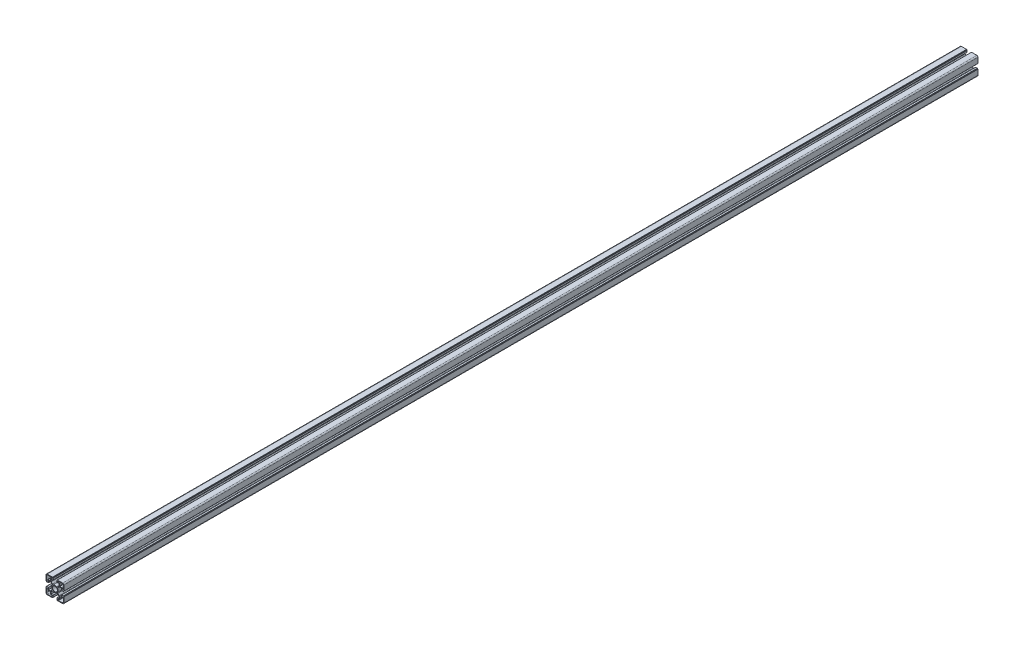
SolidWorks part; units mm, degrees
ref_plane "Front Plane" through (0, 0, 0) normal (0, 0, 1) x (1, 0, 0)
ref_plane "Top Plane" through (0, 0, 0) normal (0, 1, 0) x (1, 0, 0)
ref_plane "Right Plane" through (0, 0, 0) normal (1, 0, 0) x (0, 0, -1)
sketch "Sketch1" plane through (0, 0, 0) normal (0, 0, 1) x (1, 0, 0)
  line L3 (-22.5, 19.5) -> (-22.5, 6.3)
  line L4 (-20.7, 5) -> (-16.7, 5)
  line L5 (-16.5, 5.2) -> (-16.5, 9.8)
  line L6 (-16.3, 10) -> (-11.8642, 10)
  line L7 (-10.4924, 9.4318) -> (-7.2967, 6.236)
  line L8 (-21, 18.5) -> (-21, 9)
  line L9 (-16.5, 5) -> (-16.5, 10) construction
  line L10 (-18, 9) -> (-18, 10.5)
  line L11 (-17, 11.5) -> (-12.5, 11.5)
  line L12 (-22, 5.8) -> (-21.3, 5.8)
  line L13 (-21, 5.5) -> (-21, 5.3)
  line L14 (-21, 22.5) -> (-21, 6.5) construction
  line L15 (-18, 11.5) -> (-10.4393, 11.5) construction
  line L16 (-10.4393, 11.5) -> (-5.1016, 6.1623) construction
  line L17 (-18, 6.5) -> (-18, 11.5) construction
  line L18 (-22.5, 22.5) -> (-22.5, 5) construction
  line L19 (-22.5, 5) -> (-16.5, 5) construction
  line L20 (-21, 6.5) -> (-18, 6.5) construction
  line L21 (-16.5, 10) -> (-11.0607, 10) construction
  line L22 (-11.0607, 10) -> (-6.1623, 5.1016) construction
  line L23 (-5.5, 21) -> (-5.3, 21)
  line L24 (-5.8, 22) -> (-5.8, 21.3)
  line L25 (-11.5, 17) -> (-11.5, 12.5)
  line L26 (-9, 18) -> (-10.5, 18)
  line L27 (-18.5, 21) -> (-9, 21)
  line L28 (-9.4318, 10.4924) -> (-6.236, 7.2967)
  line L29 (-10, 16.3) -> (-10, 11.8642)
  line L30 (-5.2, 16.5) -> (-9.8, 16.5)
  line L31 (-5, 20.7) -> (-5, 16.7)
  line L32 (-19.5, 22.5) -> (-6.3, 22.5)
  line L33 (19.5, 22.5) -> (6.3, 22.5)
  line L34 (5, 20.7) -> (5, 16.7)
  line L35 (5.2, 16.5) -> (9.8, 16.5)
  line L36 (10, 16.3) -> (10, 11.8642)
  line L37 (9.4318, 10.4924) -> (6.236, 7.2967)
  line L38 (18.5, 21) -> (9, 21)
  line L39 (9, 18) -> (10.5, 18)
  line L40 (11.5, 17) -> (11.5, 12.5)
  line L41 (5.8, 22) -> (5.8, 21.3)
  line L42 (5.5, 21) -> (5.3, 21)
  line L43 (21, 5.5) -> (21, 5.3)
  line L44 (22, 5.8) -> (21.3, 5.8)
  line L45 (17, 11.5) -> (12.5, 11.5)
  line L46 (18, 9) -> (18, 10.5)
  line L47 (21, 18.5) -> (21, 9)
  line L48 (10.4924, 9.4318) -> (7.2967, 6.236)
  line L49 (16.3, 10) -> (11.8642, 10)
  line L50 (16.5, 5.2) -> (16.5, 9.8)
  line L51 (20.7, 5) -> (16.7, 5)
  line L52 (22.5, 19.5) -> (22.5, 6.3)
  line L53 (22.5, -19.5) -> (22.5, -6.3)
  line L54 (20.7, -5) -> (16.7, -5)
  line L55 (16.5, -5.2) -> (16.5, -9.8)
  line L56 (16.3, -10) -> (11.8642, -10)
  line L57 (10.4924, -9.4318) -> (7.2967, -6.236)
  line L58 (21, -18.5) -> (21, -9)
  line L59 (18, -9) -> (18, -10.5)
  line L60 (17, -11.5) -> (12.5, -11.5)
  line L61 (22, -5.8) -> (21.3, -5.8)
  line L62 (21, -5.5) -> (21, -5.3)
  line L63 (5.5, -21) -> (5.3, -21)
  line L64 (5.8, -22) -> (5.8, -21.3)
  line L65 (11.5, -17) -> (11.5, -12.5)
  line L66 (9, -18) -> (10.5, -18)
  line L67 (18.5, -21) -> (9, -21)
  line L68 (9.4318, -10.4924) -> (6.236, -7.2967)
  line L69 (10, -16.3) -> (10, -11.8642)
  line L70 (5.2, -16.5) -> (9.8, -16.5)
  line L71 (5, -20.7) -> (5, -16.7)
  line L72 (19.5, -22.5) -> (6.3, -22.5)
  line L73 (-19.5, -22.5) -> (-6.3, -22.5)
  line L74 (-5, -20.7) -> (-5, -16.7)
  line L75 (-5.2, -16.5) -> (-9.8, -16.5)
  line L76 (-10, -16.3) -> (-10, -11.8642)
  line L77 (-9.4318, -10.4924) -> (-6.236, -7.2967)
  line L78 (-18.5, -21) -> (-9, -21)
  line L79 (-9, -18) -> (-10.5, -18)
  line L80 (-11.5, -17) -> (-11.5, -12.5)
  line L81 (-5.8, -22) -> (-5.8, -21.3)
  line L82 (-5.5, -21) -> (-5.3, -21)
  line L83 (-21, -5.5) -> (-21, -5.3)
  line L84 (-22, -5.8) -> (-21.3, -5.8)
  line L85 (-17, -11.5) -> (-12.5, -11.5)
  line L86 (-18, -9) -> (-18, -10.5)
  line L87 (-21, -18.5) -> (-21, -9)
  line L88 (-10.4924, -9.4318) -> (-7.2967, -6.236)
  line L89 (-16.3, -10) -> (-11.8642, -10)
  line L90 (-16.5, -5.2) -> (-16.5, -9.8)
  line L91 (-20.7, -5) -> (-16.7, -5)
  line L92 (-22.5, -19.5) -> (-22.5, -6.3)
  arc A0 (0, 6.1) -> (-6.1, 0) centre (0, 0) ccw
  arc A1 (-6.9766, 3.9149) -> (-8, 0) centre (0, 0) ccw
  arc A2 (-21, 9) -> (-18, 9) centre (-19.5, 9) ccw
  arc A3 (-22, 5.8) -> (-22.5, 6.3) centre (-22, 6.3) cw
  arc A4 (-21, 5.3) -> (-20.7, 5) centre (-20.7, 5.3) ccw
  arc A5 (-21.3, 5.8) -> (-21, 5.5) centre (-21.3, 5.5) cw
  arc A6 (-16.7, 5) -> (-16.5, 5.2) centre (-16.7, 5.2) ccw
  arc A7 (-16.5, 9.8) -> (-16.3, 10) centre (-16.3, 9.8) cw
  arc A8 (-7.2967, 6.236) -> (-6.9766, 3.9149) centre (-8.6685, 4.8643) cw
  arc A9 (-11.8642, 10) -> (-10.4924, 9.4318) centre (-11.8642, 8.06) cw
  arc A10 (-18, 10.5) -> (-17, 11.5) centre (-17, 10.5) cw
  arc A11 (-10.5, 18) -> (-11.5, 17) centre (-10.5, 17) ccw
  arc A12 (-10, 11.8642) -> (-9.4318, 10.4924) centre (-8.06, 11.8642) ccw
  arc A13 (-6.236, 7.2967) -> (-3.9149, 6.9766) centre (-4.8643, 8.6685) ccw
  arc A14 (-9.8, 16.5) -> (-10, 16.3) centre (-9.8, 16.3) ccw
  arc A15 (-5, 16.7) -> (-5.2, 16.5) centre (-5.2, 16.7) cw
  arc A16 (-5.8, 21.3) -> (-5.5, 21) centre (-5.5, 21.3) ccw
  arc A17 (-5.3, 21) -> (-5, 20.7) centre (-5.3, 20.7) cw
  arc A18 (-5.8, 22) -> (-6.3, 22.5) centre (-6.3, 22) ccw
  arc A19 (-9, 21) -> (-9, 18) centre (-9, 19.5) cw
  arc A20 (-3.9149, 6.9766) -> (0, 8) centre (0, 0) cw
  arc A21 (-21, 18.5) -> (-18.5, 21) centre (-18.5, 18.5) cw
  arc A22 (-22.5, 19.5) -> (-19.5, 22.5) centre (-19.5, 19.5) cw
  arc A23 (-12.5, 11.5) -> (-11.5, 12.5) centre (-12.5, 12.5) ccw
  arc A24 (6.1, 0) -> (0, 6.1) centre (0, 0) ccw
  arc A25 (3.9149, 6.9766) -> (0, 8) centre (0, 0) ccw
  arc A26 (9, 21) -> (9, 18) centre (9, 19.5) ccw
  arc A27 (5.8, 22) -> (6.3, 22.5) centre (6.3, 22) cw
  arc A28 (5.3, 21) -> (5, 20.7) centre (5.3, 20.7) ccw
  arc A29 (5.8, 21.3) -> (5.5, 21) centre (5.5, 21.3) cw
  arc A30 (5, 16.7) -> (5.2, 16.5) centre (5.2, 16.7) ccw
  arc A31 (9.8, 16.5) -> (10, 16.3) centre (9.8, 16.3) cw
  arc A32 (6.236, 7.2967) -> (3.9149, 6.9766) centre (4.8643, 8.6685) cw
  arc A33 (10, 11.8642) -> (9.4318, 10.4924) centre (8.06, 11.8642) cw
  arc A34 (10.5, 18) -> (11.5, 17) centre (10.5, 17) cw
  arc A35 (18, 10.5) -> (17, 11.5) centre (17, 10.5) ccw
  arc A36 (11.8642, 10) -> (10.4924, 9.4318) centre (11.8642, 8.06) ccw
  arc A37 (7.2967, 6.236) -> (6.9766, 3.9149) centre (8.6685, 4.8643) ccw
  arc A38 (16.5, 9.8) -> (16.3, 10) centre (16.3, 9.8) ccw
  arc A39 (16.7, 5) -> (16.5, 5.2) centre (16.7, 5.2) cw
  arc A40 (21.3, 5.8) -> (21, 5.5) centre (21.3, 5.5) ccw
  arc A41 (21, 5.3) -> (20.7, 5) centre (20.7, 5.3) cw
  arc A42 (22, 5.8) -> (22.5, 6.3) centre (22, 6.3) ccw
  arc A43 (21, 9) -> (18, 9) centre (19.5, 9) cw
  arc A44 (6.9766, 3.9149) -> (8, 0) centre (0, 0) cw
  arc A45 (18.5, 21) -> (21, 18.5) centre (18.5, 18.5) cw
  arc A46 (19.5, 22.5) -> (22.5, 19.5) centre (19.5, 19.5) cw
  arc A47 (11.5, 12.5) -> (12.5, 11.5) centre (12.5, 12.5) ccw
  arc A48 (0, -6.1) -> (6.1, 0) centre (0, 0) ccw
  arc A49 (6.9766, -3.9149) -> (8, 0) centre (0, 0) ccw
  arc A50 (21, -9) -> (18, -9) centre (19.5, -9) ccw
  arc A51 (22, -5.8) -> (22.5, -6.3) centre (22, -6.3) cw
  arc A52 (21, -5.3) -> (20.7, -5) centre (20.7, -5.3) ccw
  arc A53 (21.3, -5.8) -> (21, -5.5) centre (21.3, -5.5) cw
  arc A54 (16.7, -5) -> (16.5, -5.2) centre (16.7, -5.2) ccw
  arc A55 (16.5, -9.8) -> (16.3, -10) centre (16.3, -9.8) cw
  arc A56 (7.2967, -6.236) -> (6.9766, -3.9149) centre (8.6685, -4.8643) cw
  arc A57 (11.8642, -10) -> (10.4924, -9.4318) centre (11.8642, -8.06) cw
  arc A58 (18, -10.5) -> (17, -11.5) centre (17, -10.5) cw
  arc A59 (10.5, -18) -> (11.5, -17) centre (10.5, -17) ccw
  arc A60 (10, -11.8642) -> (9.4318, -10.4924) centre (8.06, -11.8642) ccw
  arc A61 (6.236, -7.2967) -> (3.9149, -6.9766) centre (4.8643, -8.6685) ccw
  arc A62 (9.8, -16.5) -> (10, -16.3) centre (9.8, -16.3) ccw
  arc A63 (5, -16.7) -> (5.2, -16.5) centre (5.2, -16.7) cw
  arc A64 (5.8, -21.3) -> (5.5, -21) centre (5.5, -21.3) ccw
  arc A65 (5.3, -21) -> (5, -20.7) centre (5.3, -20.7) cw
  arc A66 (5.8, -22) -> (6.3, -22.5) centre (6.3, -22) ccw
  arc A67 (9, -21) -> (9, -18) centre (9, -19.5) cw
  arc A68 (3.9149, -6.9766) -> (0, -8) centre (0, 0) cw
  arc A69 (21, -18.5) -> (18.5, -21) centre (18.5, -18.5) cw
  arc A70 (22.5, -19.5) -> (19.5, -22.5) centre (19.5, -19.5) cw
  arc A71 (12.5, -11.5) -> (11.5, -12.5) centre (12.5, -12.5) ccw
  arc A72 (-6.1, 0) -> (0, -6.1) centre (0, 0) ccw
  arc A73 (-3.9149, -6.9766) -> (0, -8) centre (0, 0) ccw
  arc A74 (-9, -21) -> (-9, -18) centre (-9, -19.5) ccw
  arc A75 (-5.8, -22) -> (-6.3, -22.5) centre (-6.3, -22) cw
  arc A76 (-5.3, -21) -> (-5, -20.7) centre (-5.3, -20.7) ccw
  arc A77 (-5.8, -21.3) -> (-5.5, -21) centre (-5.5, -21.3) cw
  arc A78 (-5, -16.7) -> (-5.2, -16.5) centre (-5.2, -16.7) ccw
  arc A79 (-9.8, -16.5) -> (-10, -16.3) centre (-9.8, -16.3) cw
  arc A80 (-6.236, -7.2967) -> (-3.9149, -6.9766) centre (-4.8643, -8.6685) cw
  arc A81 (-10, -11.8642) -> (-9.4318, -10.4924) centre (-8.06, -11.8642) cw
  arc A82 (-10.5, -18) -> (-11.5, -17) centre (-10.5, -17) cw
  arc A83 (-18, -10.5) -> (-17, -11.5) centre (-17, -10.5) ccw
  arc A84 (-11.8642, -10) -> (-10.4924, -9.4318) centre (-11.8642, -8.06) ccw
  arc A85 (-7.2967, -6.236) -> (-6.9766, -3.9149) centre (-8.6685, -4.8643) ccw
  arc A86 (-16.5, -9.8) -> (-16.3, -10) centre (-16.3, -9.8) ccw
  arc A87 (-16.7, -5) -> (-16.5, -5.2) centre (-16.7, -5.2) cw
  arc A88 (-21.3, -5.8) -> (-21, -5.5) centre (-21.3, -5.5) ccw
  arc A89 (-21, -5.3) -> (-20.7, -5) centre (-20.7, -5.3) cw
  arc A90 (-22, -5.8) -> (-22.5, -6.3) centre (-22, -6.3) ccw
  arc A91 (-21, -9) -> (-18, -9) centre (-19.5, -9) cw
  arc A92 (-6.9766, -3.9149) -> (-8, 0) centre (0, 0) cw
  arc A93 (-18.5, -21) -> (-21, -18.5) centre (-18.5, -18.5) cw
  arc A94 (-19.5, -22.5) -> (-22.5, -19.5) centre (-19.5, -19.5) cw
  arc A95 (-11.5, -12.5) -> (-12.5, -11.5) centre (-12.5, -12.5) ccw
  point P24 (-5.8, 21)
  point P32 (-22.5, 5.8)
  point P35 (-21, 5)
  point P38 (-21, 5.8)
  point P83 (-5, 21)
  point P84 (-5.8, 22.5)
  point P87 (-21, 21)
  point P93 (-11.5, 11.5)
  point P102 (21, 5.8)
  point P158 (21, 5)
  point P159 (22.5, 5.8)
  point P172 (5.8, -21)
  point P228 (5, -21)
  point P229 (5.8, -22.5)
  point P242 (-21, -5.8)
  point P298 (-21, -5)
  point P299 (-22.5, -5.8)
  dimension "D11" = 0.5
  dimension "D12" = 0.3
  dimension "D13" = 0.2
  dimension "D14" = 0.2
  dimension "D6" = 1.94
  dimension "D15" = 1
  dimension "D16" = 2.5
  dimension "D4" = 3
  dimension "D17" = 1
  dimension "D5" = 0.8
  dimension "D7" = 1.5
  dimension "D9" = 1.5
  dimension "D10" = 4
  dimension "D18" = 4
extrude "Boss-Extrude1" add sketch "Sketch1" along normal blind 2303.1426
scale "Scale1" scale about centroid uniform scaling yes scale factor 0.564444
